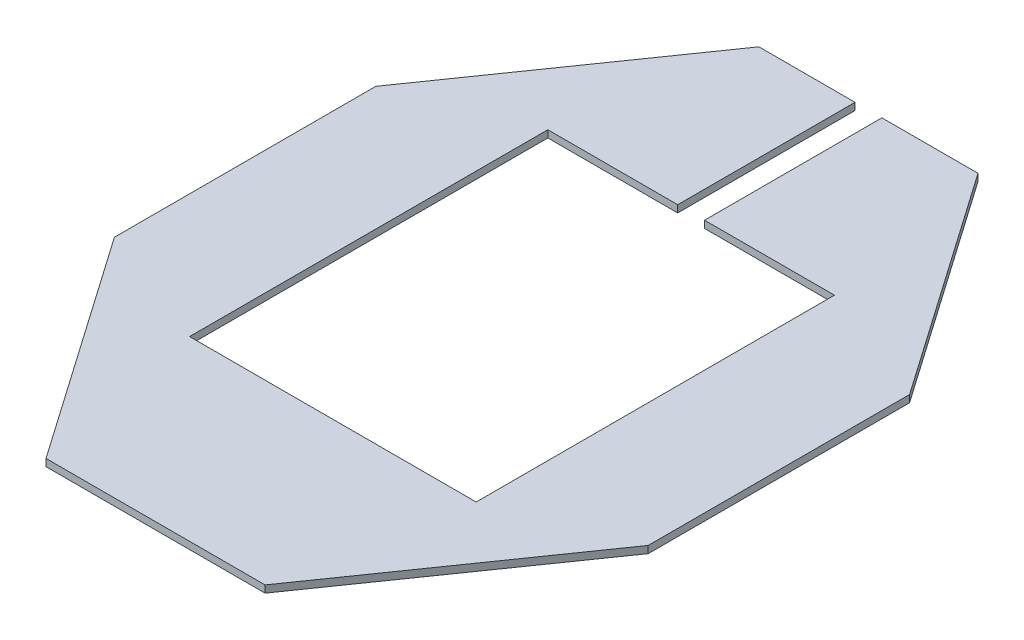
SolidWorks part; units mm, degrees
ref_plane "Front Plane" through (0, 0, 0) normal (0, 0, 1) x (1, 0, 0)
ref_plane "Top Plane" through (0, 0, 0) normal (0, 1, 0) x (1, 0, 0)
ref_plane "Right Plane" through (0, 0, 0) normal (1, 0, 0) x (0, 0, -1)
sketch "Sketch1" plane through (0, 0, 0) normal (0, 1, 0) x (1, 0, 0)
  line L0 (-16.5, 21.5) -> (16.5, 21.5)
  line L5 (16.5, 21.5) -> (16.5, -21.5)
  line L6 (-16.5, -21.5) -> (16.5, -21.5)
  line L7 (-16.5, 21.5) -> (-16.5, -21.5)
extrude "Boss-Extrude1" add sketch "Sketch1" along normal blind 0.65
sketch "Sketch2" plane through (0, 0, 0) normal (0, -1, 0) x (1, 0, 0)
  line L0 (5, 21.5) -> (16.5, 21.5)
  line L1 (16.5, -5) -> (16.5, -21.5)
  line L2 (-5, -21.5) -> (-16.5, -21.5)
  line L3 (-16.5, 5) -> (-16.5, 21.5)
  line L8 (-5, -20) -> (-5, -21.5)
  line L9 (5, -20) -> (5, -21.5)
  line L10 (-16.5, 21.5) -> (16.5, 21.5) construction
  line L11 (15, -5) -> (16.5, -5)
  line L12 (-16.5, -21.5) -> (-16.5, 21.5) construction
  line L13 (16.5, 21.5) -> (16.5, -21.5) construction
  line L14 (15, -20) -> (15, 20)
  line L15 (-15, -20) -> (15, -20)
  line L16 (-15, 20) -> (-15, -20)
  line L17 (15, 20) -> (-15, 20)
  line L18 (15, -5) -> (15, 5)
  line L19 (-5, -20) -> (5, -20)
  line L20 (-15, 5) -> (-15, -5)
  line L21 (5, 20) -> (-5, 20)
  line L22 (16.5, -21.5) -> (-16.5, -21.5) construction
  line L23 (-16.5, 21.5) -> (-5, 21.5)
  line L24 (-16.5, -21.5) -> (-16.5, -5)
  line L25 (16.5, 21.5) -> (16.5, 5)
  line L26 (16.5, -21.5) -> (5, -21.5)
  line L27 (-5, 21.5) -> (-5, 20)
  line L28 (5, 21.5) -> (5, 20)
  line L29 (-16.5, 5) -> (-15, 5)
  line L30 (-16.5, -5) -> (-15, -5)
  line L31 (15, 5) -> (16.5, 5)
  dimension "D2" = 5
  dimension "D3" = 5
  dimension "D4" = 5
  dimension "D5" = 5
  dimension "D1" = 1.5
extrude "Cut-Extrude1" cut sketch "Sketch2" against normal blind 0.25
sketch "Sketch3" plane through (0, 0.25, 0) normal (0, -1, 0) x (1, 0, 0)
  line L1 (-8, -10) -> (8, -10)
  line L2 (-8, -10) -> (-8, 10)
  line L3 (-8, 10) -> (8, 10)
  line L4 (8, -10) -> (8, 10)
  dimension "D1" = 20
  dimension "D2" = 10
  dimension "D3" = 16
  dimension "D4" = 8
extrude "Cut-Extrude2" cut sketch "Sketch3" against normal blind 4.125
sketch "Sketch4" plane through (0, 0.25, 0) normal (0, -1, 0) x (1, 0, 0)
  line L0 (-5, 21.5) -> (-16.5, 5)
  line L1 (5, 21.5) -> (16.5, 5)
  line L2 (-16.5, -5) -> (-5, -21.5)
  line L3 (16.5, -5) -> (5, -21.5)
  line L4 (-16.5, 5) -> (-16.5, 21.5)
  line L5 (-16.5, 21.5) -> (-5, 21.5)
  line L6 (5, 21.5) -> (16.5, 21.5)
  line L7 (16.5, 21.5) -> (16.5, 5)
  line L8 (16.5, -5) -> (16.5, -21.5)
  line L9 (16.5, -21.5) -> (5, -21.5)
  line L10 (-16.5, -5) -> (-16.5, -21.5)
  line L11 (-16.5, -21.5) -> (-5, -21.5)
extrude "Cut-Extrude3" cut sketch "Sketch4" against normal blind 4.125
sketch "Sketch5" plane through (0, 0.25, 0) normal (0, -1, 0) x (1, 0, 0)
  line L1 (-8, -10) -> (8, -10) construction
  line L2 (-0.75, -10) -> (0.75, -10)
  line L3 (-0.75, -10) -> (-0.75, -20)
  line L4 (-0.75, -20) -> (0.75, -20)
  line L6 (0.75, -10) -> (0.75, -20)
  line L7 (-5, -20) -> (5, -20) construction
  dimension "D1" = 0.75
  dimension "D2" = 0.75
extrude "Cut-Extrude4" cut sketch "Sketch5" against normal blind 10
sketch "Sketch6" plane through (0, 0.25, 0) normal (0, -1, 0) x (1, 0, 0)
  line L0 (0.75, -20) -> (5, -20) construction
  line L1 (5, 20) -> (-5, 20) construction
  line L2 (14.9, 11.7881) -> (22.2077, 11.7881)
  line L3 (14.9, 11.7881) -> (14.9, -11.1791)
  line L4 (14.9, -11.1791) -> (22.2077, -11.1791)
  line L5 (22.2077, 11.7881) -> (22.2077, -11.1791)
  line L6 (10.5231, 28.2935) -> (-10.2726, 28.2935)
  line L7 (10.5231, 28.2935) -> (10.5231, 19.9)
  line L8 (10.5231, 19.9) -> (-10.2726, 19.9)
  line L9 (-10.2726, -26.1959) -> (9.2703, -26.1959)
  line L10 (-10.2726, 28.2935) -> (-10.2726, 19.9)
  line L11 (15, -5) -> (15, 5) construction
  line L12 (-10.2726, -26.1959) -> (-10.2726, -19.9)
  line L13 (-10.2726, -19.9) -> (9.2703, -19.9)
  line L14 (9.2703, -26.1959) -> (9.2703, -19.9)
  line L15 (-20.9961, -11.1791) -> (-14.9, -11.1791)
  line L16 (-20.9961, -11.1791) -> (-20.9961, 11.7881)
  line L17 (-20.9961, 11.7881) -> (-14.9, 11.7881)
  line L18 (-14.9, -11.1791) -> (-14.9, 11.7881)
  line L19 (-15, 5) -> (-15, -5) construction
  dimension "D1" = 0.1
  dimension "D2" = 0.1
  dimension "D3" = 0.1
  dimension "D4" = 0.1
extrude "Cut-Extrude5" cut sketch "Sketch6" against normal mid plane 10
